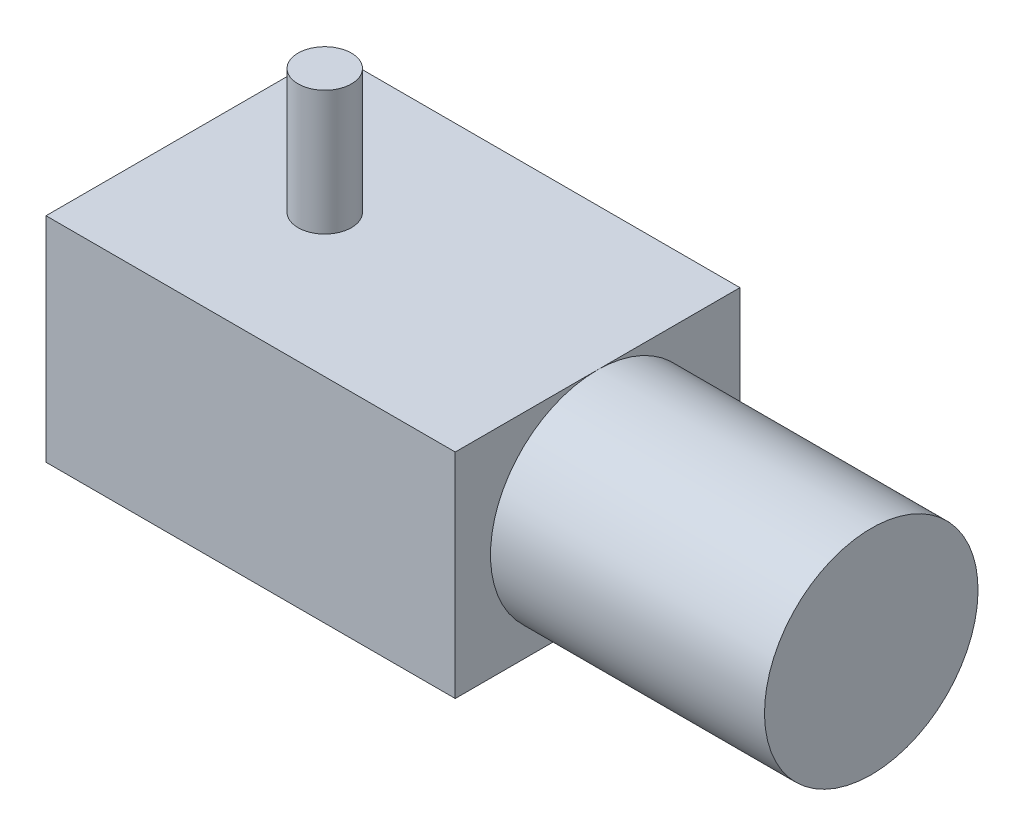
SolidWorks part; units mm, degrees
ref_plane "Front Plane" through (0, 0, 0) normal (0, 0, 1) x (1, 0, 0)
ref_plane "Top Plane" through (0, 0, 0) normal (0, 1, 0) x (1, 0, 0)
ref_plane "Right Plane" through (0, 0, 0) normal (1, 0, 0) x (0, 0, -1)
sketch "Sketch1" plane through (0, 0, 0) normal (0, 1, 0) x (1, 0, 0)
  line L1 (0, 0) -> (-76.8, 0)
  line L2 (0, 0) -> (0, 32)
  line L3 (0, 32) -> (-76.8, 32)
  line L4 (-76.8, 0) -> (-76.8, 32)
  dimension "D1" = 76.8
  dimension "D2" = 32
extrude "Boss-Extrude1" add sketch "Sketch1" along normal blind 24
sketch "Sketch2" plane through (0, 24, 0) normal (0, 1, 0) x (1, 0, 0)
  line L0 (-76.8, 32) -> (-51.2, 32) construction
  line L1 (0, 32) -> (-76.8, 32) construction
  line L2 (-76.8, 32) -> (-76.8, 0) construction
  circle A0 centre (-61.4667, 16) radius 3
  point P9 (-51.2, 32)
  point P10 (-61.4667, 16)
  dimension "D2" = 16
  dimension "D3" = 15.3333
extrude "Boss-Extrude2" add sketch "Sketch2" along normal blind 14
sketch "Sketch3" plane through (0, 0, 0) normal (1, 0, 0) x (0, 0, -1)
  line L0 (15.9606, 24) -> (0, 24)
  line L1 (0, 24) -> (0, 0)
  line L2 (0, 0) -> (15.9606, -0.0008)
  line L3 (15.9606, -0.0008) -> (32, 0)
  line L4 (32, 0) -> (32, 24)
  line L5 (32, 24) -> (15.9606, 24)
  circle A1 centre (15.9606, 11.9996) radius 12.0004
  line M2 (0, 0) -> (32, 0)
  line M3 (32, 0) -> (32, 24)
  line M4 (32, 24) -> (0, 24)
  line M5 (0, 24) -> (0, 0)
extrude "Cut-Extrude1" cut sketch "Sketch3" against normal blind 30.8 contours A1 M4 M5 M2 | A1 M2 M3 M4
equation "\"30.8.000000mm\"=14"
